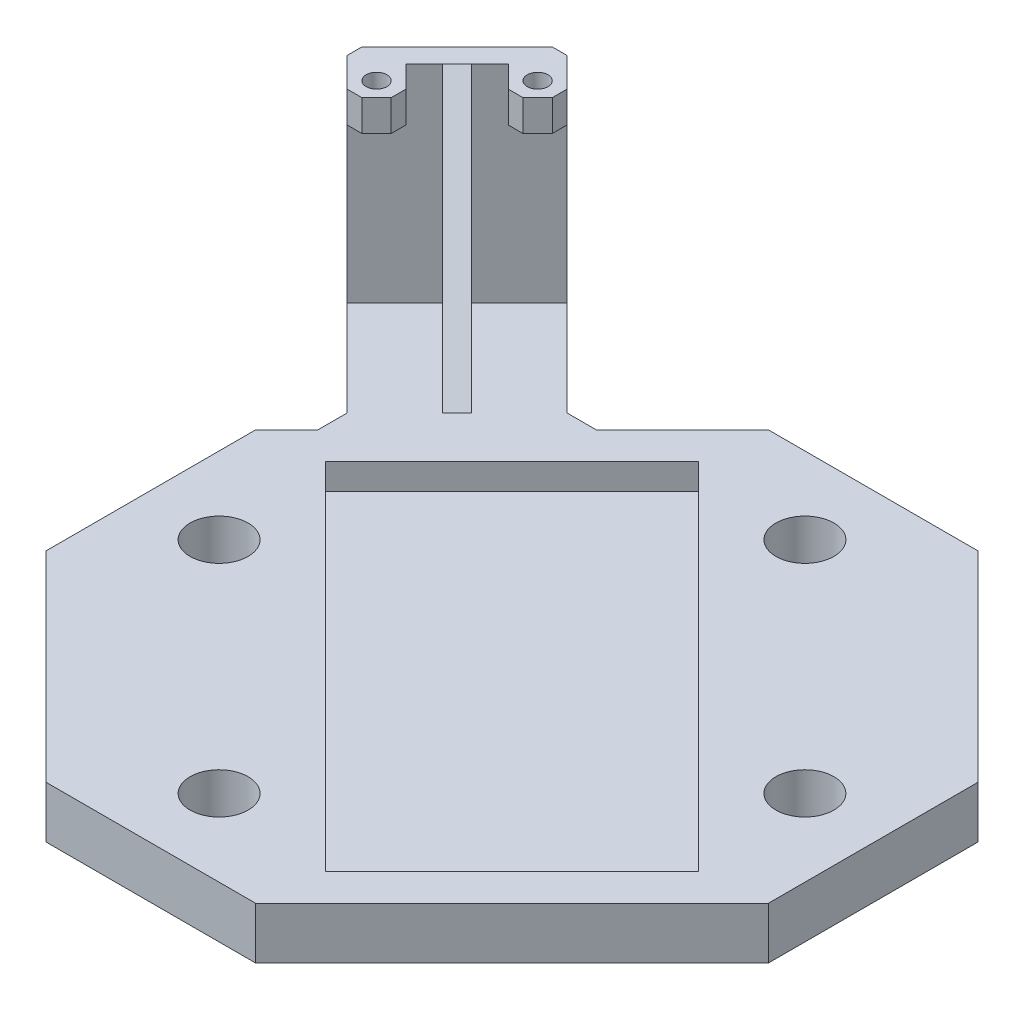
SolidWorks part; units mm, degrees
ref_plane "Front Plane" through (0, 0, 0) normal (0, 0, 1) x (1, 0, 0)
ref_plane "Top Plane" through (0, 0, 0) normal (0, 1, 0) x (1, 0, 0)
ref_plane "Right Plane" through (0, 0, 0) normal (1, 0, 0) x (0, 0, -1)
sketch "Sketch1" plane through (0, 0, 0) normal (0, 1, 0) x (1, 0, 0)
  line L0 (-40.3039, 15.5552) -> (-15.5552, 40.3039)
  line L1 (-40.3039, -40.3039) -> (40.3039, -40.3039) construction
  line L2 (-40.3039, -40.3039) -> (-40.3039, 40.3039) construction
  line L3 (-40.3039, 40.3039) -> (40.3039, 40.3039) construction
  line L4 (40.3039, -40.3039) -> (40.3039, 40.3039) construction
  line L5 (-40.3039, -40.3039) -> (40.3039, 40.3039) construction
  line L6 (-40.3039, 40.3039) -> (40.3039, -40.3039) construction
  line L7 (-27.9296, 27.9296) -> (2.476, -2.476) construction
  line L8 (-11.6661, -16.6182) -> (16.6182, 11.6661) construction
  line L9 (-11.6661, -16.6182) -> (-32.8793, 4.5951) construction
  line L10 (16.6182, 11.6661) -> (-4.5951, 32.8793) construction
  line L11 (-40.3039, 15.5552) -> (-40.3039, -4.6948)
  line L12 (-15.5552, 40.3039) -> (4.6948, 40.3039)
  line L13 (24.0428, 0.706) -> (24.0428, 20.956)
  line L14 (-0.706, -24.0428) -> (-20.956, -24.0428)
  line L15 (-32.8793, 4.5951) -> (-4.5951, 32.8793) construction
  line L16 (-18.7372, 18.7372) -> (11.6684, -11.6684) construction
  line L17 (-0.706, -24.0428) -> (24.0428, 0.706)
  line L18 (-40.3039, -4.6948) -> (-20.956, -24.0428)
  line L19 (4.6948, 40.3039) -> (24.0428, 20.956)
  circle A0 centre (-11.6661, -16.6182) radius 2.8
  circle A1 centre (16.6182, 11.6661) radius 2.8
  circle A2 centre (-4.5951, 32.8793) radius 2.8
  circle A3 centre (-32.8793, 4.5951) radius 2.8
  point P0 (0, 0)
  point P13 (2.476, -2.476)
  point P28 (11.6684, -11.6684)
  dimension "D6" = 5.6
  dimension "D1" = 135
  dimension "D2" = 35
  dimension "D3" = 43
  dimension "D4" = 40
  dimension "D5" = 30
  dimension "D7" = 20.25
  dimension "D8" = 20.25
  dimension "D9" = 43
  dimension "D10" = 35
  dimension "D11" = 20.25
  dimension "D12" = 20.25
extrude "Boss-Extrude1" add sketch "Sketch1" along normal blind 5
sketch "Sketch2" plane through (0, 5, 0) normal (0, 1, 0) x (1, 0, 0)
  line L0 (-27.9296, 27.9296) -> (11.6684, -11.6684) construction
  line L1 (-15.5552, 40.3039) -> (-40.3039, 15.5552) construction
  line L2 (-0.706, -24.0428) -> (24.0428, 0.706) construction
  line L3 (-17.1462, -0.885) -> (0.885, 17.1462) construction
  line L4 (0.0011, -18.0324) -> (-34.2935, 16.2623)
  line L5 (18.0324, -0.0011) -> (-16.2623, 34.2935)
  line L6 (-34.2935, 16.2623) -> (-16.2623, 34.2935)
  line L7 (0.0011, -18.0324) -> (18.0324, -0.0011)
  point P9 (-8.1306, 8.1306)
  point P12 (-17.1462, -0.885)
  point P15 (0.885, 17.1462)
  dimension "D1" = 25.5
  dimension "D2" = 48.5
extrude "Cut-Extrude1" cut sketch "Sketch2" against normal blind 2.5
sketch "Sketch3" plane through (-27.9296, 0, -27.9296) normal (-0.7071, 0, -0.7071) x (-0.7071, 0, 0.7071)
  line L1 (-17.5, 5) -> (17.5, 5)
  line L2 (-17.5, 5) -> (-17.5, 0)
  line L3 (-17.5, 0) -> (17.5, 0)
  line L4 (17.5, 5) -> (17.5, 0)
extrude "Boss-Extrude2" add sketch "Sketch3" along normal blind 17
sketch "Sketch4" plane through (0, 5, 0) normal (0, 1, 0) x (1, 0, 0)
  line L0 (-52.3248, 27.576) -> (-50.9105, 26.1618)
  line L1 (-52.3248, 27.576) -> (-40.3039, 15.5552) construction
  line L2 (-50.9105, 26.1618) -> (-26.1618, 50.9105)
  line L3 (-27.576, 52.3248) -> (-15.5552, 40.3039) construction
  line L4 (-26.1618, 50.9105) -> (-27.576, 52.3248)
  line L5 (-27.576, 52.3248) -> (-52.3248, 27.576)
  dimension "D1" = 2
extrude "Boss-Extrude3" add sketch "Sketch4" along normal blind 20
sketch "Sketch9" plane through (0, 5, 0) normal (0, 1, 0) x (1, 0, 0)
  line L0 (-34.2935, 16.2623) -> (-48.966, 30.9348) construction
  line L1 (-34.2935, 16.2623) -> (0.0011, -18.0324) construction
  line L2 (-27.576, 52.3248) -> (-52.3248, 27.576) construction
sketch "Sketch5" plane through (-38.5362, 0, -38.5362) normal (0.7071, 0, 0.7071) x (0.7071, 0, -0.7071)
  line L0 (-12.75, 25) -> (-11.25, 25) construction
  line L1 (-17.5, 25) -> (17.5, 25) construction
  line L2 (-7.25, 25) -> (-0.25, 25) construction
  line L3 (-11.25, 25) -> (-7.25, 25)
  line L4 (-11.25, 25) -> (-11.25, 22)
  line L5 (-11.25, 22) -> (-7.25, 22)
  line L6 (-7.25, 25) -> (-7.25, 22)
  line L7 (-0.25, 25) -> (3.75, 25)
  line L8 (3.75, 25) -> (3.75, 22)
  line L9 (3.75, 22) -> (-0.25, 22)
  line L10 (-0.25, 22) -> (-0.25, 25)
  line L11 (-12.75, 25) -> (-12.75, 5) construction
  dimension "D1" = 1.5
  dimension "D2" = 3
  dimension "D3" = 4
  dimension "D4" = 7
  dimension "D5" = 3
  dimension "D6" = 4
extrude "Boss-Extrude4" add sketch "Sketch5" along normal blind 4
sketch "Sketch6" plane through (0, 25, 0) normal (0, 1, 0) x (1, 0, 0)
  line L0 (-46.4911, 30.5812) -> (-43.6627, 33.4097) construction
  line L1 (-38.713, 38.3594) -> (-35.8845, 41.1878) construction
  line L2 (-45.0769, 31.9954) -> (-42.2485, 29.167) construction
  line L3 (-40.8343, 30.5812) -> (-43.6627, 27.7528) construction
  line L4 (-37.2987, 39.7736) -> (-34.4703, 36.9452) construction
  line L5 (-33.0561, 38.3594) -> (-35.8845, 35.531) construction
  circle A0 centre (-43.6627, 30.5812) radius 1
  circle A1 centre (-35.8845, 38.3594) radius 1
  dimension "D1" = 2
extrude "Cut-Extrude2" cut sketch "Sketch6" against normal up to next
sketch "Sketch12" plane through (-38.5362, 0, -38.5362) normal (0.7071, 0, 0.7071) x (0.7071, 0, -0.7071)
  line L5 (-17.5, 5) -> (17.5, 5) construction
  line L6 (-11.25, 5) -> (-11.25, 25)
  line L10 (-11.25, 25) -> (-17.5, 25)
  line L11 (-17.5, 25) -> (-17.5, 5)
  line L12 (-17.5, 5) -> (-11.25, 5)
  line L13 (3.75, 25) -> (3.75, 5)
  line L14 (3.75, 5) -> (17.5, 5)
  line L15 (17.5, 5) -> (17.5, 25)
  line L16 (17.5, 25) -> (3.75, 25)
extrude "Cut-Extrude5" cut sketch "Sketch12" against normal up to next
sketch "Sketch13" plane through (0, 5, 0) normal (0, 1, 0) x (1, 0, 0)
  line L0 (-50.9105, 26.1618) -> (-40.3039, 15.5552)
  line L2 (-50.9105, 26.1618) -> (-46.4911, 30.5812) construction
  line L3 (-52.3248, 27.576) -> (-40.3039, 15.5552) construction
  line L4 (-40.3039, 15.5552) -> (-35.8845, 19.9746)
  line L5 (-35.8845, 19.9746) -> (-46.4911, 30.5812)
  line L6 (-46.4911, 30.5812) -> (-50.9105, 26.1618)
  line L7 (-50.9105, 26.1618) -> (-52.3248, 27.576)
  line L8 (-52.3248, 27.576) -> (-47.9053, 31.9954)
  line L9 (-47.9053, 31.9954) -> (-46.4911, 30.5812)
  line L10 (-37.2987, 42.602) -> (-27.576, 52.3248)
  line L11 (-27.576, 52.3248) -> (-15.5552, 40.3039)
  line L12 (-15.5552, 40.3039) -> (-25.2779, 30.5812)
  line L13 (-37.2987, 42.602) -> (-25.2779, 30.5812)
  line M16 (-46.4911, 30.5812) -> (-47.9053, 31.9954)
  line M17 (-47.9053, 31.9954) -> (-52.3248, 27.576)
  line M18 (-52.3248, 27.576) -> (-40.3039, 15.5552)
  line M26 (-15.5552, 40.3039) -> (-27.576, 52.3248)
  line M27 (-27.576, 52.3248) -> (-37.2987, 42.602)
  line M28 (-37.2987, 42.602) -> (-35.8845, 41.1878)
extrude "Cut-Extrude6" cut sketch "Sketch13" against normal up to next contours L6 M16 M17 M18 | L5 L6 L4 M18 | L13 L12 M28 M26 M27
chamfer "Chamfer6" distance 2 angle 45 2 edges at (-25.2779, 2.5, -30.5812) (-35.8845, 2.5, -19.9746)
chamfer "Chamfer7" distance 1 angle 45 2 edges at (-37.2987, 12.5, -42.602) (-47.9053, 12.5, -31.9954)
chamfer "Chamfer8" distance 1 angle 45 4 edges at (-33.0561, 23.5, -38.3594) (-35.8845, 23.5, -35.531) (-40.8343, 23.5, -30.5812) (-43.6627, 23.5, -27.7528)
ref_plane "Plane1" through (-2.6517, 0, 2.6517) normal (-0.7071, 0, 0.7071) x (0.7071, 0, 0.7071)
sketch "Sketch15" plane through (-38.5362, 0, -38.5362) normal (0.7071, 0, 0.7071) x (0.7071, 0, -0.7071)
  line L0 (-7.25, 25) -> (-0.25, 25) construction
  point P0 (-3.75, 25)
sketch "Sketch16" plane through (0, 5, 0) normal (0, 1, 0) x (1, 0, 0)
  line L0 (-37.2987, 21.3888) -> (-26.6921, 31.9954) construction
  point P4 (-31.9954, 26.6921)
sketch "Sketch17" plane through (-2.6517, 0, 2.6517) normal (-0.7071, 0, 0.7071) x (0.7071, 0, 0.7071)
  line L0 (-54.4984, 25) -> (-41.4984, 5)
rib "Rib1" sketch "Sketch17" sketch "Sketch17" thickness 2 extrusion direction parallel to sketch draft on no parameters "D1"=2
